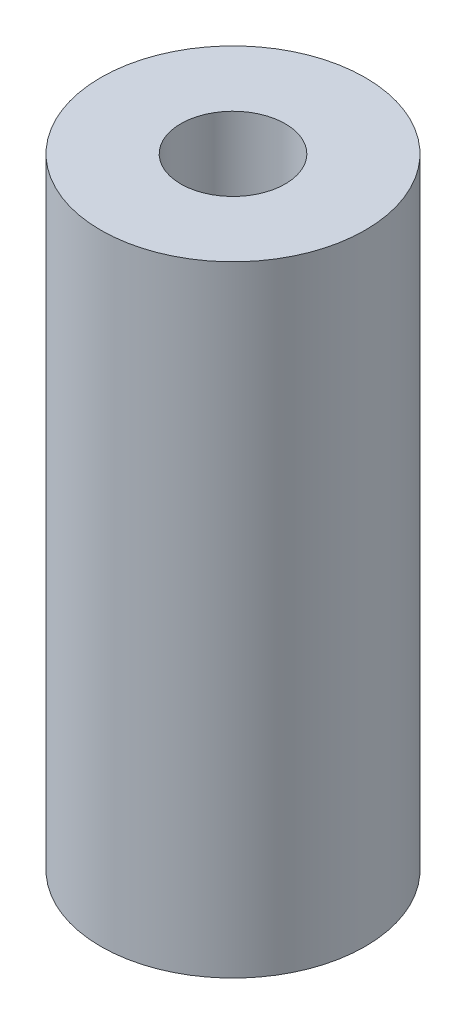
SolidWorks part; units mm, degrees
ref_plane "Front Plane" through (0, 0, 0) normal (0, 0, 1) x (1, 0, 0)
ref_plane "Top Plane" through (0, 0, 0) normal (0, 1, 0) x (1, 0, 0)
ref_plane "Right Plane" through (0, 0, 0) normal (1, 0, 0) x (0, 0, -1)
sketch "Sketch1" plane through (0, 0, 0) normal (0, 1, 0) x (1, 0, 0)
  circle A0 centre (0, 0) radius 4.05
  circle A1 centre (0, 0) radius 1.6
  dimension "D1" = 8.1
  dimension "D2" = 3.2
extrude "Boss-Extrude1" add sketch "Sketch1" along normal blind 19
